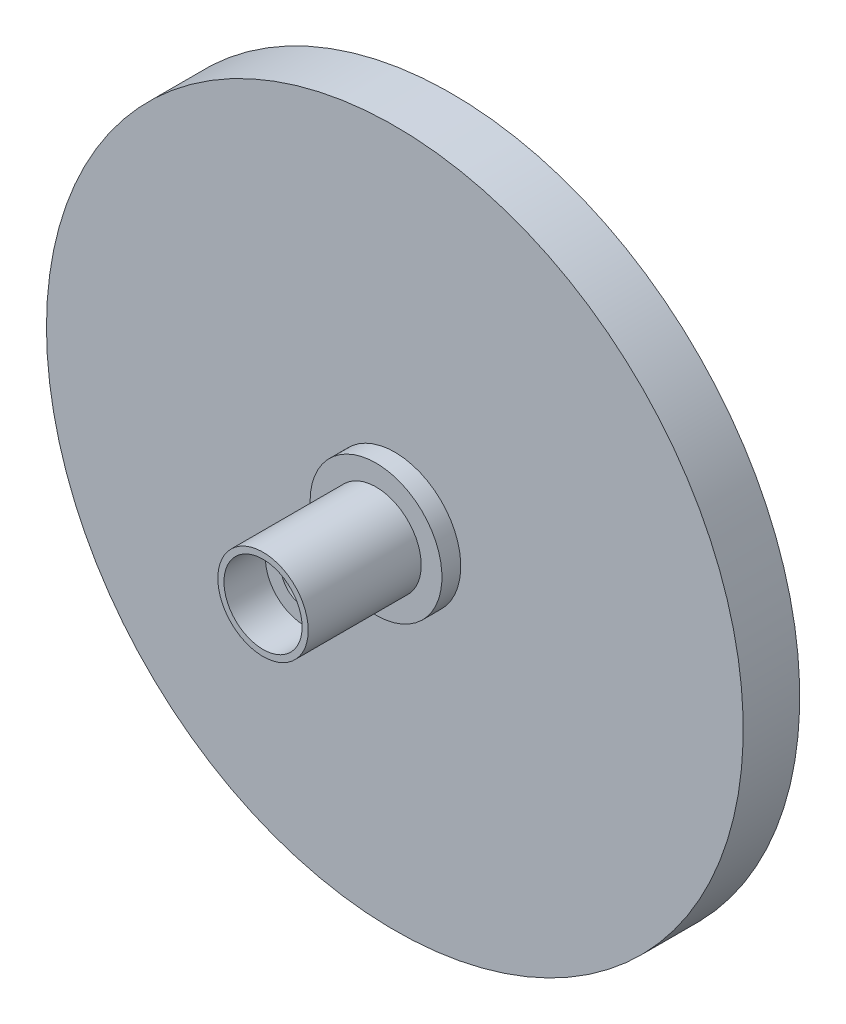
SolidWorks part; units mm, degrees
ref_plane "Alzado" through (0, 0, 0) normal (0, 0, 1) x (1, 0, 0)
ref_plane "Planta" through (0, 0, 0) normal (0, 1, 0) x (1, 0, 0)
ref_plane "Vista lateral" through (0, 0, 0) normal (1, 0, 0) x (0, 0, -1)
sketch "Croquis1" plane through (0, 0, 0) normal (0, 0, 1) x (1, 0, 0)
  circle A0 centre (0, 0) radius 2.4
  dimension "D1" = 4.8
extrude "Saliente-Extruir1" add sketch "Croquis1" along normal blind 6
sketch "Croquis2" plane through (0, 0, 0) normal (0, 0, -1) x (-1, 0, 0)
  circle A0 centre (0, 0) radius 3.5
  dimension "D1" = 7
extrude "Saliente-Extruir2" add sketch "Croquis2" along normal blind 1
sketch "Croquis3" plane through (0, 0, -1) normal (0, 0, -1) x (-1, 0, 0)
  circle A0 centre (0, 0) radius 18.5
  dimension "D1" = 37
extrude "Saliente-Extruir3" add sketch "Croquis3" along normal blind 3
sketch "Croquis4" plane through (0, 0, -4) normal (0, 0, -1) x (-1, 0, 0)
  line L0 (0, 0) -> (0, 15.3311) construction
  line L1 (0, 15.3311) -> (-1.6817, 12.4183)
  line L3 (0, 15.3311) -> (1.6817, 12.4183)
  arc A0 (-1.4082, 12.1453) -> (0, 12.5245) centre (0.0013, 9.7157) cw
  arc A1 (-1.6817, 12.4183) -> (-1.4082, 12.1453) centre (-1.5085, 12.3183) ccw
  arc A3 (1.6817, 12.4183) -> (1.4082, 12.1453) centre (1.5085, 12.3183) cw
  arc A4 (1.4082, 12.1453) -> (0, 12.5245) centre (-0.0013, 9.7157) ccw
  dimension "D3" = 0.2
  dimension "D1" = 30
extrude "Cortar-Extruir1" cut sketch "Croquis4" against normal blind 2
sketch "Croquis5" plane through (0, 0, 6) normal (0, 0, 1) x (1, 0, 0)
  circle A0 centre (0, 0) radius 2.075
  dimension "D1" = 4.15
extrude "Cortar-Extruir2" cut sketch "Croquis5" against normal blind 2.2
sketch "Croquis6" plane through (0, 0, 3.8) normal (0, 0, 1) x (1, 0, 0)
  circle A0 centre (0, 0) radius 1.25
  dimension "D1" = 2.5
extrude "Cortar-Extruir3" cut sketch "Croquis6" against normal through all
